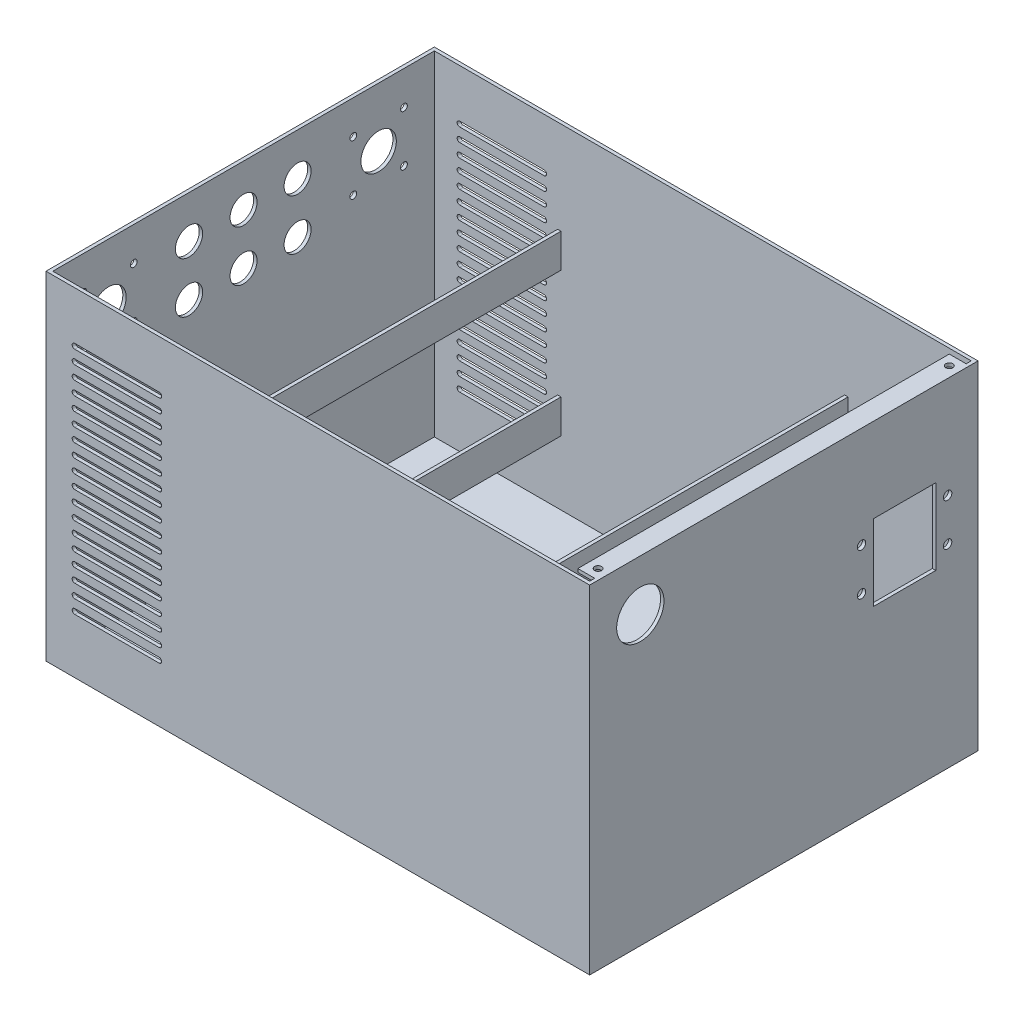
SolidWorks part; units mm, degrees
ref_plane "前视基准面" through (0, 0, 0) normal (0, 0, 1) x (1, 0, 0)
ref_plane "上视基准面" through (0, 0, 0) normal (0, 1, 0) x (1, 0, 0)
ref_plane "右视基准面" through (0, 0, 0) normal (1, 0, 0) x (0, 0, -1)
sketch "草图2" plane through (0, 0, 0) normal (0, 1, 0) x (1, 0, 0)
  line L1 (-160, 115) -> (160, 115)
  line L2 (-160, 115) -> (-160, -115)
  line L3 (-160, -115) -> (160, -115)
  line L4 (160, 115) -> (160, -115)
  line L5 (-160, 115) -> (160, -115) construction
  line L6 (-160, -115) -> (160, 115) construction
  point P0 (0, 0)
  dimension "D1" = 320
  dimension "D2" = 230
extrude "凸台-拉伸1" add sketch "草图2" along normal blind 200
sketch "草图3" plane through (0, 200, 0) normal (0, 1, 0) x (1, 0, 0)
  line L0 (-160, 115) -> (-160, -115) construction
  line L1 (-160, 113) -> (158, 113)
  line L2 (-160, 113) -> (-160, -113)
  line L3 (-160, -113) -> (158, -113)
  line L4 (158, 113) -> (158, -113)
  line L5 (160, 115) -> (-160, 115) construction
  dimension "D1" = 318
  dimension "D2" = 226
  dimension "D3" = 2
extrude "切除-拉伸2" cut sketch "草图3" against normal blind 200
sketch "草图4" plane through (0, 200, 0) normal (0, 1, 0) x (1, 0, 0)
  line L0 (158, -113) -> (158, 113) construction
  line L1 (158, 110) -> (148, 110)
  line L2 (158, 110) -> (158, -110)
  line L3 (158, -110) -> (148, -110)
  line L4 (148, 110) -> (148, -110)
  line L5 (158, 113) -> (-160, 113) construction
  dimension "D1" = 10
  dimension "D2" = 220
  dimension "D3" = 3
extrude "凸台-拉伸2" add sketch "草图4" against normal blind 2
sketch "草图5" plane through (0, 200, 0) normal (0, 1, 0) x (1, 0, 0)
  line L0 (148, 110) -> (148, -110) construction
  line L1 (158, 110) -> (148, 110) construction
  circle A0 centre (154, 104) radius 2.1
  dimension "D1" = 4.2
  dimension "D2" = 6
  dimension "D3" = 6
extrude "切除-拉伸3" cut sketch "草图5" against normal blind 2
sketch "草图6" plane through (0, 200, 0) normal (0, 1, 0) x (1, 0, 0)
  line L0 (148, 110) -> (148, -110) construction
  line L1 (148, -110) -> (158, -110) construction
  circle A0 centre (154, -104) radius 2.1
  dimension "D1" = 4.2
  dimension "D2" = 6
  dimension "D3" = 6
extrude "切除-拉伸4" cut sketch "草图6" against normal blind 2
sketch "草图13" plane through (0, 0, 115) normal (0, 0, 1) x (1, 0, 0)
  line L0 (-145, 170) -> (-95, 170) construction
  line L1 (-145, 171.5) -> (-95, 171.5)
  line L2 (-145, 168.5) -> (-95, 168.5)
  line L3 (-160, 200) -> (160, 200) construction
  line L4 (-160, 200) -> (-160, 0) construction
  line L5 (-145, 162) -> (-95, 162) construction
  line L6 (-145, 163.5) -> (-95, 163.5)
  line L7 (-145, 160.5) -> (-95, 160.5)
  line L8 (-145, 154) -> (-95, 154) construction
  line L9 (-145, 155.5) -> (-95, 155.5)
  line L10 (-145, 152.5) -> (-95, 152.5)
  line L11 (-145, 146) -> (-95, 146) construction
  line L12 (-145, 147.5) -> (-95, 147.5)
  line L13 (-145, 144.5) -> (-95, 144.5)
  line L14 (-145, 138) -> (-95, 138) construction
  line L15 (-145, 139.5) -> (-95, 139.5)
  line L16 (-145, 136.5) -> (-95, 136.5)
  line L17 (-145, 130) -> (-95, 130) construction
  line L18 (-145, 131.5) -> (-95, 131.5)
  line L19 (-145, 128.5) -> (-95, 128.5)
  line L20 (-145, 122) -> (-95, 122) construction
  line L21 (-145, 123.5) -> (-95, 123.5)
  line L22 (-145, 120.5) -> (-95, 120.5)
  line L23 (-145, 114) -> (-95, 114) construction
  line L24 (-145, 115.5) -> (-95, 115.5)
  line L25 (-145, 112.5) -> (-95, 112.5)
  line L26 (-145, 106) -> (-95, 106) construction
  line L27 (-145, 107.5) -> (-95, 107.5)
  line L28 (-145, 104.5) -> (-95, 104.5)
  line L29 (-145, 98) -> (-95, 98) construction
  line L30 (-145, 99.5) -> (-95, 99.5)
  line L31 (-145, 96.5) -> (-95, 96.5)
  line L32 (-145, 90) -> (-95, 90) construction
  line L33 (-145, 91.5) -> (-95, 91.5)
  line L34 (-145, 88.5) -> (-95, 88.5)
  line L35 (-145, 82) -> (-95, 82) construction
  line L36 (-145, 83.5) -> (-95, 83.5)
  line L37 (-145, 80.5) -> (-95, 80.5)
  line L38 (-145, 74) -> (-95, 74) construction
  line L39 (-145, 75.5) -> (-95, 75.5)
  line L40 (-145, 72.5) -> (-95, 72.5)
  line L41 (-145, 66) -> (-95, 66) construction
  line L42 (-145, 67.5) -> (-95, 67.5)
  line L43 (-145, 64.5) -> (-95, 64.5)
  line L44 (-145, 58) -> (-95, 58) construction
  line L45 (-145, 59.5) -> (-95, 59.5)
  line L46 (-145, 56.5) -> (-95, 56.5)
  line L47 (-145, 50) -> (-95, 50) construction
  line L48 (-145, 51.5) -> (-95, 51.5)
  line L49 (-145, 48.5) -> (-95, 48.5)
  line L50 (-145, 42) -> (-95, 42) construction
  line L51 (-145, 43.5) -> (-95, 43.5)
  line L52 (-145, 40.5) -> (-95, 40.5)
  line L53 (-145, 34) -> (-95, 34) construction
  line L54 (-145, 35.5) -> (-95, 35.5)
  line L55 (-145, 32.5) -> (-95, 32.5)
  arc A0 (-145, 171.5) -> (-145, 168.5) centre (-145, 170) ccw
  arc A1 (-95, 168.5) -> (-95, 171.5) centre (-95, 170) ccw
  arc A2 (-145, 163.5) -> (-145, 160.5) centre (-145, 162) ccw
  arc A3 (-95, 160.5) -> (-95, 163.5) centre (-95, 162) ccw
  arc A4 (-145, 155.5) -> (-145, 152.5) centre (-145, 154) ccw
  arc A5 (-95, 152.5) -> (-95, 155.5) centre (-95, 154) ccw
  arc A6 (-145, 147.5) -> (-145, 144.5) centre (-145, 146) ccw
  arc A7 (-95, 144.5) -> (-95, 147.5) centre (-95, 146) ccw
  arc A8 (-145, 139.5) -> (-145, 136.5) centre (-145, 138) ccw
  arc A9 (-95, 136.5) -> (-95, 139.5) centre (-95, 138) ccw
  arc A10 (-145, 131.5) -> (-145, 128.5) centre (-145, 130) ccw
  arc A11 (-95, 128.5) -> (-95, 131.5) centre (-95, 130) ccw
  arc A12 (-145, 123.5) -> (-145, 120.5) centre (-145, 122) ccw
  arc A13 (-95, 120.5) -> (-95, 123.5) centre (-95, 122) ccw
  arc A14 (-145, 115.5) -> (-145, 112.5) centre (-145, 114) ccw
  arc A15 (-95, 112.5) -> (-95, 115.5) centre (-95, 114) ccw
  arc A16 (-145, 107.5) -> (-145, 104.5) centre (-145, 106) ccw
  arc A17 (-95, 104.5) -> (-95, 107.5) centre (-95, 106) ccw
  arc A18 (-145, 99.5) -> (-145, 96.5) centre (-145, 98) ccw
  arc A19 (-95, 96.5) -> (-95, 99.5) centre (-95, 98) ccw
  arc A20 (-145, 91.5) -> (-145, 88.5) centre (-145, 90) ccw
  arc A21 (-95, 88.5) -> (-95, 91.5) centre (-95, 90) ccw
  arc A22 (-145, 83.5) -> (-145, 80.5) centre (-145, 82) ccw
  arc A23 (-95, 80.5) -> (-95, 83.5) centre (-95, 82) ccw
  arc A24 (-145, 75.5) -> (-145, 72.5) centre (-145, 74) ccw
  arc A25 (-95, 72.5) -> (-95, 75.5) centre (-95, 74) ccw
  arc A26 (-145, 67.5) -> (-145, 64.5) centre (-145, 66) ccw
  arc A27 (-95, 64.5) -> (-95, 67.5) centre (-95, 66) ccw
  arc A28 (-145, 59.5) -> (-145, 56.5) centre (-145, 58) ccw
  arc A29 (-95, 56.5) -> (-95, 59.5) centre (-95, 58) ccw
  arc A30 (-145, 51.5) -> (-145, 48.5) centre (-145, 50) ccw
  arc A31 (-95, 48.5) -> (-95, 51.5) centre (-95, 50) ccw
  arc A32 (-145, 43.5) -> (-145, 40.5) centre (-145, 42) ccw
  arc A33 (-95, 40.5) -> (-95, 43.5) centre (-95, 42) ccw
  arc A34 (-145, 35.5) -> (-145, 32.5) centre (-145, 34) ccw
  arc A35 (-95, 32.5) -> (-95, 35.5) centre (-95, 34) ccw
  point P2 (-120, 170)
  point P15 (-120, 162)
  point P22 (-120, 154)
  point P29 (-120, 146)
  point P36 (-120, 138)
  point P43 (-120, 130)
  point P50 (-120, 122)
  point P57 (-120, 114)
  point P64 (-120, 106)
  point P71 (-120, 98)
  point P78 (-120, 90)
  point P85 (-120, 82)
  point P92 (-120, 74)
  point P99 (-120, 66)
  point P106 (-120, 58)
  point P113 (-120, 50)
  point P120 (-120, 42)
  point P127 (-120, 34)
  dimension "D1" = 50
  dimension "D2" = 28.5
  dimension "D3" = 30
  dimension "D4" = 40
  dimension "D5" = 18
extrude "切除-拉伸10" cut sketch "草图13" against normal blind 2
sketch "草图14" plane through (0, 0, -115) normal (0, 0, -1) x (-1, 0, 0)
  line L0 (145, 170) -> (95, 170) construction
  line L1 (145, 168.5) -> (95, 168.5)
  line L2 (145, 171.5) -> (95, 171.5)
  line L3 (-160, 200) -> (160, 200) construction
  line L4 (160, 200) -> (160, 0) construction
  line L5 (145, 162) -> (95, 162) construction
  line L6 (145, 160.5) -> (95, 160.5)
  line L7 (145, 163.5) -> (95, 163.5)
  line L8 (145, 154) -> (95, 154) construction
  line L9 (145, 152.5) -> (95, 152.5)
  line L10 (145, 155.5) -> (95, 155.5)
  line L11 (145, 146) -> (95, 146) construction
  line L12 (145, 144.5) -> (95, 144.5)
  line L13 (145, 147.5) -> (95, 147.5)
  line L14 (145, 138) -> (95, 138) construction
  line L15 (145, 136.5) -> (95, 136.5)
  line L16 (145, 139.5) -> (95, 139.5)
  line L17 (145, 130) -> (95, 130) construction
  line L18 (145, 128.5) -> (95, 128.5)
  line L19 (145, 131.5) -> (95, 131.5)
  line L20 (145, 122) -> (95, 122) construction
  line L21 (145, 120.5) -> (95, 120.5)
  line L22 (145, 123.5) -> (95, 123.5)
  line L23 (145, 114) -> (95, 114) construction
  line L24 (145, 112.5) -> (95, 112.5)
  line L25 (145, 115.5) -> (95, 115.5)
  line L26 (145, 106) -> (95, 106) construction
  line L27 (145, 104.5) -> (95, 104.5)
  line L28 (145, 107.5) -> (95, 107.5)
  line L29 (145, 98) -> (95, 98) construction
  line L30 (145, 96.5) -> (95, 96.5)
  line L31 (145, 99.5) -> (95, 99.5)
  line L32 (145, 90) -> (95, 90) construction
  line L33 (145, 88.5) -> (95, 88.5)
  line L34 (145, 91.5) -> (95, 91.5)
  line L35 (145, 82) -> (95, 82) construction
  line L36 (145, 80.5) -> (95, 80.5)
  line L37 (145, 83.5) -> (95, 83.5)
  line L38 (145, 74) -> (95, 74) construction
  line L39 (145, 72.5) -> (95, 72.5)
  line L40 (145, 75.5) -> (95, 75.5)
  line L41 (145, 66) -> (95, 66) construction
  line L42 (145, 64.5) -> (95, 64.5)
  line L43 (145, 67.5) -> (95, 67.5)
  line L44 (145, 58) -> (95, 58) construction
  line L45 (145, 56.5) -> (95, 56.5)
  line L46 (145, 59.5) -> (95, 59.5)
  line L47 (145, 50) -> (95, 50) construction
  line L48 (145, 48.5) -> (95, 48.5)
  line L49 (145, 51.5) -> (95, 51.5)
  line L50 (145, 42) -> (95, 42) construction
  line L51 (145, 40.5) -> (95, 40.5)
  line L52 (145, 43.5) -> (95, 43.5)
  line L53 (145, 34) -> (95, 34) construction
  line L54 (145, 32.5) -> (95, 32.5)
  line L55 (145, 35.5) -> (95, 35.5)
  arc A0 (145, 168.5) -> (145, 171.5) centre (145, 170) ccw
  arc A1 (95, 171.5) -> (95, 168.5) centre (95, 170) ccw
  arc A2 (145, 160.5) -> (145, 163.5) centre (145, 162) ccw
  arc A3 (95, 163.5) -> (95, 160.5) centre (95, 162) ccw
  arc A4 (145, 152.5) -> (145, 155.5) centre (145, 154) ccw
  arc A5 (95, 155.5) -> (95, 152.5) centre (95, 154) ccw
  arc A6 (145, 144.5) -> (145, 147.5) centre (145, 146) ccw
  arc A7 (95, 147.5) -> (95, 144.5) centre (95, 146) ccw
  arc A8 (145, 136.5) -> (145, 139.5) centre (145, 138) ccw
  arc A9 (95, 139.5) -> (95, 136.5) centre (95, 138) ccw
  arc A10 (145, 128.5) -> (145, 131.5) centre (145, 130) ccw
  arc A11 (95, 131.5) -> (95, 128.5) centre (95, 130) ccw
  arc A12 (145, 120.5) -> (145, 123.5) centre (145, 122) ccw
  arc A13 (95, 123.5) -> (95, 120.5) centre (95, 122) ccw
  arc A14 (145, 112.5) -> (145, 115.5) centre (145, 114) ccw
  arc A15 (95, 115.5) -> (95, 112.5) centre (95, 114) ccw
  arc A16 (145, 104.5) -> (145, 107.5) centre (145, 106) ccw
  arc A17 (95, 107.5) -> (95, 104.5) centre (95, 106) ccw
  arc A18 (145, 96.5) -> (145, 99.5) centre (145, 98) ccw
  arc A19 (95, 99.5) -> (95, 96.5) centre (95, 98) ccw
  arc A20 (145, 88.5) -> (145, 91.5) centre (145, 90) ccw
  arc A21 (95, 91.5) -> (95, 88.5) centre (95, 90) ccw
  arc A22 (145, 80.5) -> (145, 83.5) centre (145, 82) ccw
  arc A23 (95, 83.5) -> (95, 80.5) centre (95, 82) ccw
  arc A24 (145, 72.5) -> (145, 75.5) centre (145, 74) ccw
  arc A25 (95, 75.5) -> (95, 72.5) centre (95, 74) ccw
  arc A26 (145, 64.5) -> (145, 67.5) centre (145, 66) ccw
  arc A27 (95, 67.5) -> (95, 64.5) centre (95, 66) ccw
  arc A28 (145, 56.5) -> (145, 59.5) centre (145, 58) ccw
  arc A29 (95, 59.5) -> (95, 56.5) centre (95, 58) ccw
  arc A30 (145, 48.5) -> (145, 51.5) centre (145, 50) ccw
  arc A31 (95, 51.5) -> (95, 48.5) centre (95, 50) ccw
  arc A32 (145, 40.5) -> (145, 43.5) centre (145, 42) ccw
  arc A33 (95, 43.5) -> (95, 40.5) centre (95, 42) ccw
  arc A34 (145, 32.5) -> (145, 35.5) centre (145, 34) ccw
  arc A35 (95, 35.5) -> (95, 32.5) centre (95, 34) ccw
  point P2 (120, 170)
  point P15 (120, 162)
  point P22 (120, 154)
  point P29 (120, 146)
  point P36 (120, 138)
  point P43 (120, 130)
  point P50 (120, 122)
  point P57 (120, 114)
  point P64 (120, 106)
  point P71 (120, 98)
  point P78 (120, 90)
  point P85 (120, 82)
  point P92 (120, 74)
  point P99 (120, 66)
  point P106 (120, 58)
  point P113 (120, 50)
  point P120 (120, 42)
  point P127 (120, 34)
  dimension "D1" = 30
  dimension "D2" = 1.5
  dimension "D3" = 40
  dimension "D4" = 50
  dimension "D5" = 18
extrude "切除-拉伸11" cut sketch "草图14" against normal blind 2
sketch "草图15" plane through (160, 0, 0) normal (1, 0, 0) x (0, 0, -1)
  line L0 (-115, 200) -> (115, 200) construction
  line L1 (-115, 200) -> (-115, 0) construction
  circle A0 centre (-85, 170) radius 14
  dimension "D1" = 28
  dimension "D2" = 30
  dimension "D3" = 30
extrude "切除-拉伸12" cut sketch "草图15" against normal blind 2
sketch "草图19" plane through (0, 0, 0) normal (0, -1, 0) x (1, 0, 0)
  line L0 (160, -115) -> (-160, -115) construction
  line L1 (-160, 115) -> (160, 115)
  line L2 (-160, 115) -> (-160, -115)
  line L3 (-160, -115) -> (160, -115)
  line L4 (160, 115) -> (160, -115)
  line L5 (-160, 115) -> (160, -115) construction
  line L6 (-160, -115) -> (160, 115) construction
  point P0 (0, 0)
  dimension "D1" = 320
  dimension "D2" = 230
extrude "凸台-拉伸7" add sketch "草图19" against normal blind 2
sketch "草图20" plane through (-160, 0, 0) normal (-1, 0, 0) x (0, 0, 1)
  line L1 (-115, 200) -> (115, 200)
  line L2 (-115, 200) -> (-115, 0)
  line L3 (-115, 0) -> (115, 0)
  line L4 (115, 200) -> (115, 0)
extrude "凸台-拉伸8" add sketch "草图20" along normal blind 2
sketch "草图23" plane through (0, 0, 115) normal (0, 0, 1) x (1, 0, 0)
  line L0 (160, 200) -> (160, 0) construction
  line L1 (83, 60) -> (85, 60)
  line L2 (83, 60) -> (83, 40)
  line L3 (83, 40) -> (85, 40)
  line L4 (85, 60) -> (85, 40)
  line L5 (-162, 0) -> (160, 0) construction
  dimension "D1" = 2
  dimension "D2" = 20
  dimension "D3" = 75
  dimension "D4" = 40
extrude "凸台-拉伸11" add sketch "草图23" against normal blind 230
sketch "草图24" plane through (0, 0, 115) normal (0, 0, 1) x (1, 0, 0)
  line L0 (-162, 0) -> (-162, 200) construction
  line L1 (-87, 60) -> (-85, 60)
  line L2 (-87, 60) -> (-87, 40)
  line L3 (-87, 40) -> (-85, 40)
  line L4 (-85, 60) -> (-85, 40)
  line L5 (-162, 0) -> (160, 0) construction
  dimension "D1" = 2
  dimension "D2" = 20
  dimension "D3" = 75
  dimension "D4" = 40
extrude "凸台-拉伸12" add sketch "草图24" against normal blind 230
sketch "草图25" plane through (0, 0, 115) normal (0, 0, 1) x (1, 0, 0)
  line L0 (160, 200) -> (160, 0) construction
  line L1 (83, 145) -> (85, 145)
  line L2 (83, 145) -> (83, 125)
  line L3 (83, 125) -> (85, 125)
  line L4 (85, 145) -> (85, 125)
  line L5 (-162, 0) -> (160, 0) construction
  dimension "D1" = 2
  dimension "D2" = 20
  dimension "D3" = 75
  dimension "D4" = 125
extrude "凸台-拉伸13" add sketch "草图25" against normal blind 230
sketch "草图26" plane through (0, 0, 115) normal (0, 0, 1) x (1, 0, 0)
  line L0 (-162, 0) -> (-162, 200) construction
  line L1 (-87, 145) -> (-85, 145)
  line L2 (-87, 145) -> (-87, 125)
  line L3 (-87, 125) -> (-85, 125)
  line L4 (-85, 145) -> (-85, 125)
  line L5 (-162, 200) -> (160, 200) construction
  dimension "D1" = 2
  dimension "D2" = 20
  dimension "D3" = 75
  dimension "D4" = 55
extrude "凸台-拉伸14" add sketch "草图26" against normal blind 230
sketch "草图31" plane through (-162, 0, 0) normal (-1, 0, 0) x (0, 0, 1)
  line L0 (115, 0) -> (115, 200) construction
  line L1 (115, 200) -> (-115, 200) construction
  circle A0 centre (95, 180) radius 2
  circle A1 centre (65, 180) radius 2
  circle A2 centre (65, 150) radius 2
  circle A3 centre (95, 150) radius 2
  circle A4 centre (-95, 180) radius 2
  circle A5 centre (-95, 150) radius 2
  circle A6 centre (-65, 150) radius 2
  circle A7 centre (-65, 180) radius 2
  dimension "D1" = 4
  dimension "D2" = 20
  dimension "D3" = 20
  dimension "D4" = 2
  dimension "D5" = 2
  dimension "D6" = 2
extrude "切除-拉伸21" cut sketch "草图31" against normal blind 2
sketch "草图32" plane through (-162, 0, 0) normal (-1, 0, 0) x (0, 0, 1)
  line L0 (115, 200) -> (-115, 200) construction
  line L1 (115, 0) -> (115, 200) construction
  circle A0 centre (80, 165) radius 10.5
  circle A1 centre (-80, 165) radius 10.5
  dimension "D1" = 21
  dimension "D2" = 35
  dimension "D3" = 35
  dimension "D4" = 2
extrude "切除-拉伸22" cut sketch "草图32" against normal blind 2
sketch "草图35" plane through (-162, 0, 0) normal (-1, 0, 0) x (0, 0, 1)
  line L0 (0, 200) -> (0, 0) construction
  line L1 (115, 200) -> (-115, 200) construction
  line L2 (-115, 100) -> (115, 100) construction
  line L3 (-115, 200) -> (-115, 0) construction
  line L4 (115, 0) -> (115, 200) construction
  circle A0 centre (0, 175) radius 8
  circle A1 centre (32.2948, 175) radius 8.0737
  circle A2 centre (-32.0064, 175) radius 8
  circle A3 centre (0, 145) radius 8
  circle A4 centre (-32.0064, 145) radius 8
  circle A5 centre (32.2948, 145) radius 8.0737
  dimension "D1" = 16
  dimension "D3" = 16
  dimension "D2" = 25
  dimension "D4" = 2
extrude "切除-拉伸23" cut sketch "草图35" against normal blind 2
sketch "草图36" plane through (160, 0, 0) normal (1, 0, 0) x (0, 0, -1)
  line L0 (115, 200) -> (115, 0) construction
  line L1 (53, 150) -> (90, 150)
  line L2 (53, 150) -> (53, 105)
  line L3 (53, 105) -> (90, 105)
  line L4 (90, 150) -> (90, 105)
  line L5 (-115, 200) -> (115, 200) construction
  dimension "D1" = 37
  dimension "D2" = 45
  dimension "D3" = 25
  dimension "D4" = 50
extrude "切除-拉伸24" cut sketch "草图36" against normal blind 2
sketch "草图37" plane through (160, 0, 0) normal (1, 0, 0) x (0, 0, -1)
  line L0 (53, 150) -> (53, 105) construction
  line L1 (90, 150) -> (53, 150) construction
  circle A0 centre (46, 140) radius 2.5
  circle A1 centre (97, 140) radius 2.5
  circle A2 centre (97, 115) radius 2.5
  circle A3 centre (46, 115) radius 2.5
  dimension "D1" = 5
  dimension "D2" = 7
  dimension "D3" = 10
  dimension "D4" = 2
  dimension "D5" = 2
extrude "切除-拉伸25" cut sketch "草图37" against normal blind 2
